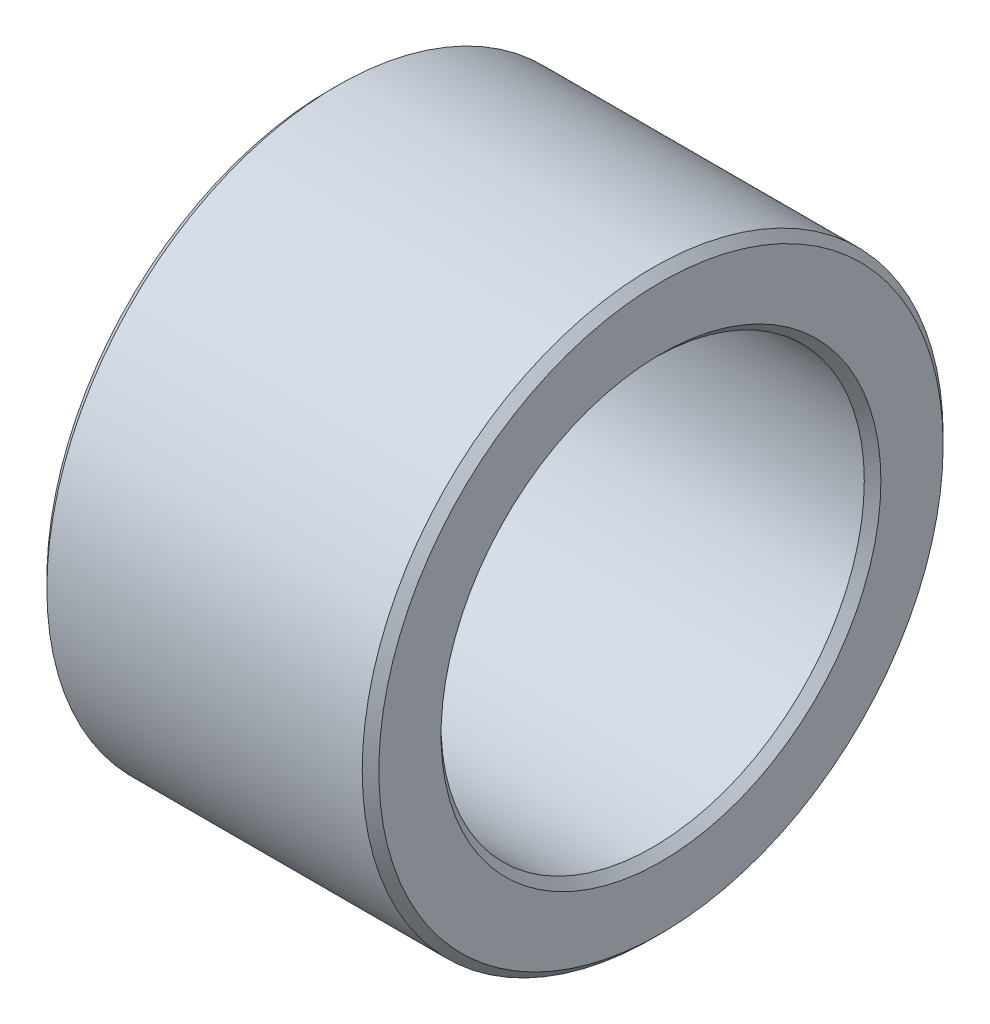
SolidWorks part; units mm, degrees
material "黄铜"
ref_plane "前视基准面" through (0, 0, 0) normal (1, 0, 0) x (0, 1, 0)
ref_plane "上视基准面" through (0, 0, 0) normal (0, 0, 1) x (0, 1, 0)
ref_plane "右视基准面" through (0, 0, 0) normal (0, 1, 0) x (-1, 0, 0)
other "Configuration Table"
sketch "草图1" plane through (0, 0, 0) normal (1, 0, 0) x (0, 1, 0)
  circle A0 centre (0, 0) radius 3.5
  circle A1 centre (0, 0) radius 2.55
  dimension "D1" = 7
  dimension "D2" = 5.1
extrude "凸台-拉伸1" add sketch "草图1" along normal blind 4
chamfer "倒角1" distance 0.1 angle 45 4 edges at (4, 0, -2.55) (0, 0, -2.55) (0, 0, -3.5) (4, 0, -3.5)
